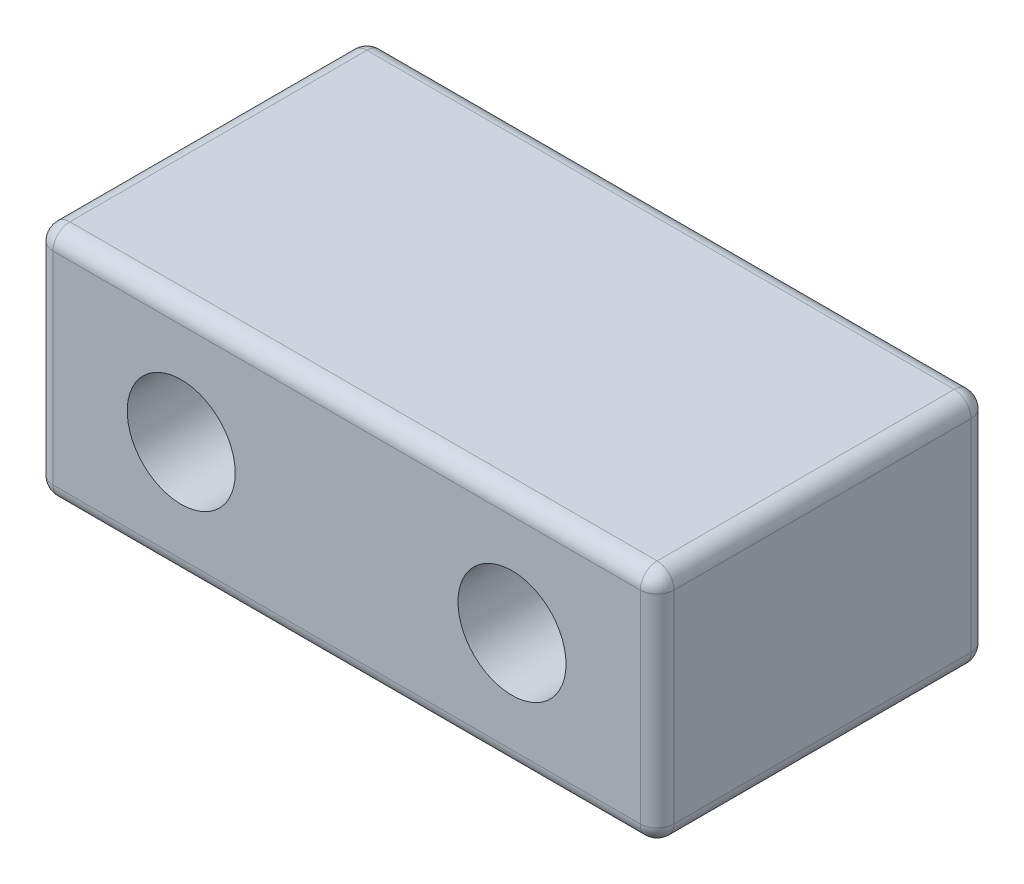
SolidWorks part; units mm, degrees
ref_plane "前视基准面" through (0, 0, 0) normal (0, 0, 1) x (1, 0, 0)
ref_plane "上视基准面" through (0, 0, 0) normal (0, 1, 0) x (1, 0, 0)
ref_plane "右视基准面" through (0, 0, 0) normal (1, 0, 0) x (0, 0, -1)
other "Configuration Table"
sketch "草图1" plane through (0, 0, 0) normal (0, 0, 1) x (1, 0, 0)
  line L1 (0, 0) -> (18.4, 0)
  line L2 (0, 0) -> (0, 7)
  line L3 (0, 7) -> (18.4, 7)
  line L4 (18.4, 0) -> (18.4, 7)
  dimension "D1" = 18.4
  dimension "D2" = 7
extrude "凸台-拉伸1" add sketch "草图1" along normal blind 9.8
sketch "草图2" plane through (0, 0, 9.8) normal (0, 0, 1) x (1, 0, 0)
  line L0 (0, 3.5) -> (18.4, 3.5) construction
  line L1 (0, 7) -> (0, 0) construction
  line L2 (18.4, 0) -> (18.4, 7) construction
  line L3 (9.2, 7) -> (9.2, 0) construction
  line L4 (18.4, 7) -> (0, 7) construction
  line L5 (0, 0) -> (18.4, 0) construction
  circle A0 centre (4.3, 3.5) radius 1.6
  circle A1 centre (14.1, 3.5) radius 1.6
  dimension "D1" = 3.2
  dimension "D2" = 9.8
extrude "切除-拉伸1" cut sketch "草图2" against normal blind 9.8
fillet "圆角1" radius 0.5 12 edges at (0, 3.5, 0) (9.2, 0, 0) (18.4, 3.5, 0) (9.2, 7, 0) (18.4, 3.5, 9.8) (9.2, 7, 9.8) (0, 7, 4.9) (18.4, 7, 4.9) (18.4, 0, 4.9) (0, 0, 4.9) (0, 3.5, 9.8) (9.2, 0, 9.8)
